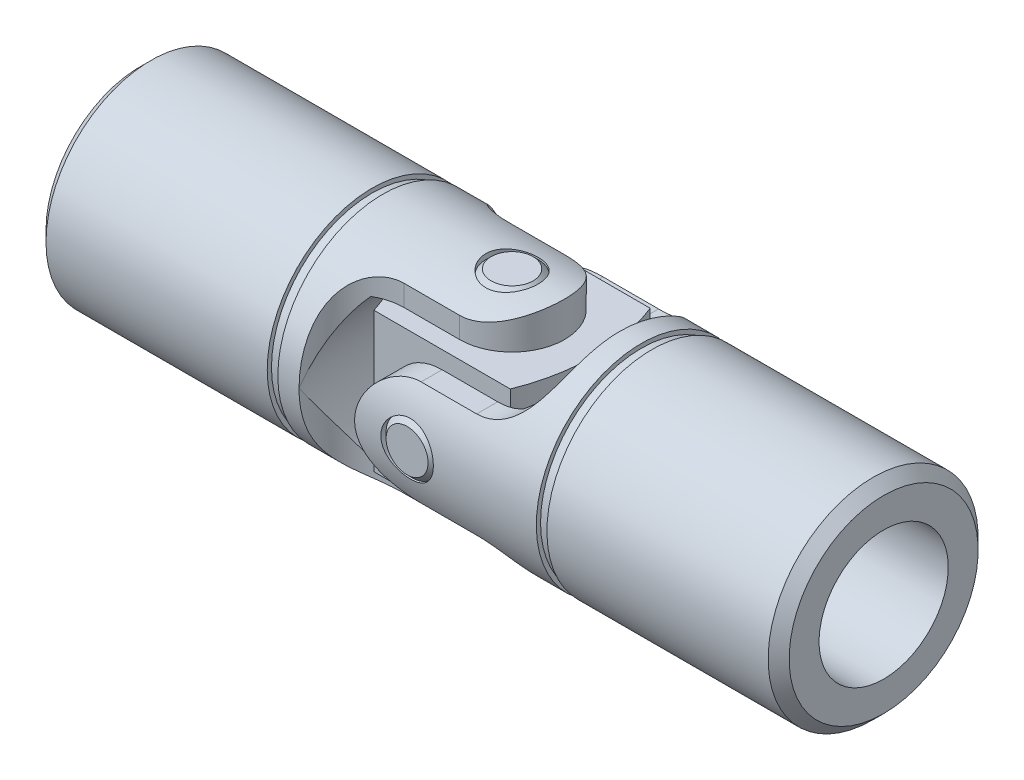
SolidWorks part; units mm, degrees
ref_plane "Front Plane" through (0, 0, 0) normal (0, 0, 1) x (1, 0, 0)
ref_plane "Top Plane" through (0, 0, 0) normal (0, 1, 0) x (1, 0, 0)
ref_plane "Right Plane" through (0, 0, 0) normal (1, 0, 0) x (0, 0, -1)
sketch "Sketch0" plane through (0, 0, 0) normal (0, 1, 0) x (1, 0, 0)
  line L0 (-36.5125, 0) -> (36.5125, 0) construction
  line L1 (-36.5125, 10.3187) -> (-36.5125, -10.3187) construction
  line L2 (-14.2875, 6.35) -> (-14.2875, -6.35) construction
  line L3 (-14.2875, 6.35) -> (-7.9375, 0) construction
  line L4 (-7.9375, 0) -> (-14.2875, -6.35) construction
  line L5 (-11.1125, 3.175) -> (-11.1125, -3.175) construction
  point P7 (-14.2875, 0)
  point P8 (0, 0)
  point P12 (-11.1125, 0)
sketch "Sketch1" plane through (0, 0, 0) normal (0, 1, 0) x (1, 0, 0)
  line L0 (-36.5125, 10.3187) -> (-13.7418, 10.3187)
  line L1 (5.1594, 10.3188) -> (5.1594, 0)
  line L2 (5.1594, 0) -> (-36.5125, 0)
  line L3 (-36.5125, 0) -> (-36.5125, 10.3187)
  line L4 (-36.5125, 10.3187) -> (-36.5125, -10.3187) construction
  line L5 (-36.5125, 0) -> (36.5125, 0) construction
  line L6 (-12.7, 10.3187) -> (5.1594, 10.3188)
  line L7 (-12.7, 3.175) -> (-12.7, 9.902) construction
  line L8 (-13.7418, 10.3187) -> (-13.7418, 9.902)
  line L9 (-13.7418, 9.902) -> (-12.7, 9.902)
  line L10 (-12.7, 10.3187) -> (-12.7, 9.902)
  line L11 (0, 0) -> (10.3187, 0) construction
  line L12 (-11.1125, 3.175) -> (-14.2875, 3.175) construction
  line L13 (-14.2875, 6.35) -> (-14.2875, -6.35) construction
  circle A0 centre (0, 0) radius 10.3187 construction
  dimension "D1" = 1.0418
  dimension "D2" = 0.4167
  dimension "D3" = 41.6719
revolve "Revolve1" add sketch "Sketch1" angle 360 about L0
chamfer "Chamfer1" distance 1.0319 angle 45 1 edges at (-36.5125, 0, 10.3187)
sketch "Sketch2" plane through (0, 0, 0) normal (0, 1, 0) x (1, 0, 0)
  line L0 (-12.7, 10.3188) -> (-10.6164, 10.3188) construction
  line L1 (-12.7, 10.3187) -> (5.1594, 10.3188) construction
  line L2 (5.1594, 10.3188) -> (-12.7, 10.3188) construction
  line L4 (-36.5125, 0) -> (5.1594, 0) construction
  line L5 (-10.6164, 10.3188) -> (10.3187, 10.3187)
  line L6 (10.3187, 10.3187) -> (10.3187, -10.3187)
  line L7 (10.3187, -10.3187) -> (-10.6164, -10.3188)
  line L8 (0, 5.1594) -> (0, 0) construction
  line L9 (0, 5.1594) -> (-5.457, 5.1594)
  line L10 (-10.6164, 10.3188) -> (-10.6164, -10.3188) construction
  line L11 (0, -5.1594) -> (-5.457, -5.1594)
  arc A0 (-10.6164, 10.3188) -> (-5.457, 5.1594) centre (-5.457, 10.3188) ccw
  arc A1 (0, -5.1594) -> (0, 5.1594) centre (0, 0) ccw
  arc A2 (-5.457, -5.1594) -> (-10.6164, -10.3188) centre (-5.457, -10.3188) ccw
  dimension "D1" = 10.3187
  dimension "D2" = 2.0836
extrude "Extrude1" cut sketch "Sketch2" against normal through all and the other way through all
sketch "Sketch3" plane through (0, 0, 0) normal (0, 0, 1) x (1, 0, 0)
  line L0 (-8.0367, 6.8723) -> (-10.6164, 4.2926) construction
  line L1 (-8.0367, 6.8723) -> (10.3187, 6.8723)
  line L2 (-10.6164, 4.2926) -> (-10.6164, -4.2926) construction
  line L3 (-8.0367, -6.8723) -> (10.3187, -6.8723)
  line L4 (10.3187, 6.8723) -> (10.3187, -6.8723)
  line L5 (-10.6164, -4.2926) -> (-8.0367, -6.8723) construction
  line L6 (-10.6164, 0) -> (-5.457, 0) construction
  line L7 (-5.457, -8.9363) -> (-5.457, 8.9363) construction
  line L8 (10.3187, 0) -> (-10.6164, 0) construction
  line L9 (-8.0367, 0) -> (-8.0367, 6.8723) construction
  arc A0 (-8.0367, 6.8723) -> (-8.0367, -6.8723) centre (-0.1727, 0) ccw
  dimension "D1" = 13.7446
extrude "Extrude3" cut sketch "Sketch3" against normal through all and the other way through all
sketch "Sketch4" plane through (-36.5125, 0, 0) normal (-1, 0, 0) x (0, 0, 1)
  circle A0 centre (0, 0) radius 6.35
extrude "Extrude4" cut sketch "Sketch4" against normal up to vertex (22.225 mm away) up to point (-14.2875, 0, -6.35)
sketch "Sketch5" plane through (-14.2875, 0, 0) normal (-1, 0, 0) x (0, 0, 1)
  circle A0 centre (0, 0) radius 6.35 construction
  circle A1 centre (0, 0) radius 6.35
extrude "Extrude5" cut sketch "Sketch5" against normal through all draft 45
sketch "Sketch6" plane through (0, 0, 0) normal (0, 1, 0) x (1, 0, 0)
  line L0 (-36.5125, 0) -> (36.5125, 0) construction
  line L1 (5.1594, 0) -> (2.5797, 0) construction
  line L2 (2.5797, 0) -> (0, 0) construction
  circle A0 centre (0, 0) radius 2.5797
  arc A1 (0, -5.1594) -> (0, 5.1594) centre (0, 0) ccw construction
  dimension "D1" = 5.1594
extrude "Extrude6" cut sketch "Sketch6" against normal through all and the other way through all
mirror "Mirror1" about plane through (0, 0, 0) normal (1, 0, 0) of bodies 109 122
move or copy body "Body-Move/Copy1" bodies to move or copy 110 copy no rotation origin (0, 0, 0) rotation axis (1, 0, 0) rotation angle 90
sketch "Sketch18" plane through (0, 0, 0) normal (0, 1, 0) x (1, 0, 0)
  line L0 (-47.625, -6.35) -> (-14.2875, -6.35)
  line L3 (-47.625, 6.35) -> (-14.2875, 6.35)
  line L4 (-14.2875, 6.35) -> (-14.2875, -6.35)
  line L5 (14.2875, 6.35) -> (14.2875, -6.35)
  line L6 (14.2875, -6.35) -> (36.5125, -6.35)
  line L7 (14.2875, 6.35) -> (36.5125, 6.35)
  line L8 (0, 0) -> (14.2875, 0) construction
  line L9 (36.5125, -9.2869) -> (36.5125, 9.2869) construction
  line L11 (-14.2875, -6.35) -> (-14.2875, 6.35) construction
sketch "Sketch10" plane through (0, 0, 0) normal (0, 0, 1) x (1, 0, 0)
  line L0 (-8.0367, 6.8723) -> (8.0367, -6.8723) construction
  line L1 (-8.0367, 6.8723) -> (8.0367, 6.8723)
  line L2 (-8.0367, 6.8723) -> (-8.0367, -6.8723)
  line L3 (-8.0367, -6.8723) -> (8.0367, -6.8723)
  line L4 (8.0367, 6.8723) -> (8.0367, -6.8723)
  line L5 (0, 6.8723) -> (5.1594, 6.8723) construction
extrude "Extrude10" add sketch "Sketch10" against normal up to surface and the other way up to surface separate body up to face at (0, 2.5797, -6.8723) other way up to face at (0, -2.5797, 6.8723)
sketch "Sketch20" plane through (0, 6.8723, 0) normal (0, 1, 0) x (1, 0, 0)
  line L4 (8.0367, 6.8723) -> (-8.0367, 6.8723) construction
  line L5 (8.0367, -6.8723) -> (-8.0367, -6.8723) construction
  line L6 (-8.0367, 6.8723) -> (-8.0367, -6.8723) construction
  line L7 (8.0367, 6.8723) -> (8.0367, -6.8723) construction
  line L8 (9.0527, -7.8883) -> (9.0527, 7.8883)
  line L9 (9.0527, 7.8883) -> (-9.0527, 7.8883)
  line L10 (-9.0527, 7.8883) -> (-9.0527, -7.8883)
  line L11 (-9.0527, -7.8883) -> (9.0527, -7.8883)
  line L12 (9.0527, -7.8883) -> (9.0527, 7.8883)
  line L13 (9.0527, 7.8883) -> (6.6973, 7.8883)
  line L14 (-9.0527, 7.8883) -> (-9.0527, -7.8883)
  line L15 (-9.0527, -7.8883) -> (-6.6973, -7.8883)
  line L16 (-6.6973, 6.8723) -> (-6.6973, 7.8883)
  line L17 (6.6973, 6.8723) -> (6.6973, 7.8883)
  line L18 (6.6973, -6.8723) -> (6.6973, -7.8883)
  line L19 (-6.6973, -6.8723) -> (-6.6973, -7.8883)
  line L20 (-6.6973, 7.8883) -> (-9.0527, 7.8883)
  line L21 (6.6973, -7.8883) -> (9.0527, -7.8883)
  line L22 (-36.5125, 0) -> (5.1594, 0) construction
  line L23 (8.0367, 6.8723) -> (-8.0367, 6.8723) construction
  arc A0 (6.6973, 6.8723) -> (6.6973, -6.8723) centre (-10.2627, 0) cw
  arc A1 (-6.6973, 6.8723) -> (-6.6973, -6.8723) centre (10.2627, 0) ccw
  dimension "D2" = 16.0734
  dimension "D3" = 1.3395
extrude "Cut-Extrude2" cut sketch "Sketch20" against normal through all
sketch "Sketch13" plane through (0, 0, 0) normal (0, 1, 0) x (1, 0, 0)
  circle A0 centre (0, 0) radius 2.5797 construction
  circle A1 centre (0, 0) radius 2.5797
extrude "Extrude13" cut sketch "Sketch13" against normal through all and the other way through all
sketch "Sketch14" plane through (0, 0, 0) normal (0, 1, 0) x (1, 0, 0)
  circle A1 centre (0, 0) radius 2.5797
  circle A2 centre (0, 0) radius 2.5797
  dimension "D1" = 0
extrude "Extrude14" add sketch "Sketch14" along normal mid plane 20.6375 separate body
sketch "Sketch15" plane through (0, 0, 0) normal (0, 0, 1) x (1, 0, 0)
  circle A0 centre (0, 0) radius 2.5797 construction
  circle A1 centre (0, 0) radius 2.5797
extrude "Extrude15" cut sketch "Sketch15" against normal through all and the other way through all
sketch "Sketch16" plane through (0, 0, 0) normal (0, 0, 1) x (1, 0, 0)
  circle A1 centre (0, 0) radius 2.5797
  circle A2 centre (0, 0) radius 2.5797
  dimension "D1" = 0
extrude "Extrude16" add sketch "Sketch16" along normal mid plane 20.6375
chamfer "Chamfer3" distance 0.5159 angle 45 4 edges at (0, -10.3187, 2.5797) (0, 10.3187, 2.5797) (2.5797, 0, 10.3187) (2.5797, 0, -10.3187)
move or copy body "Body-Move/Copy2" [suppressed] bodies to move or copy 111 copy no rotation origin (0, 0, 0) rotation axis (0, 0, -1) rotation angle 15
equation "\"D2@Sketch3\" = \"D1@Sketch3\" / 4"
equation "\"D1@Extrude14\" = \"OD@Sketch0\""
equation "\"D1@Extrude16\" = \"D1@Extrude14\""
equation "\"D1@Sketch3\" = \"OD@Sketch0\"*.666"
equation "\"D1@Sketch1\" = \"D3@Sketch1\"*.025"
equation "\"D2@Sketch1\" = \"D1@Sketch1\"/2.5"
equation "\"D1@Chamfer1\" = \"OD@Sketch0\"/20"
equation "\"D1@Chamfer3\" = \"D1@Chamfer1\"*.50"
equation "\"D2@Sketch2\" = \"D1@Sketch1\"*2"
equation "\"D3@Sketch20\" = \"D2@Sketch20\"/12"
